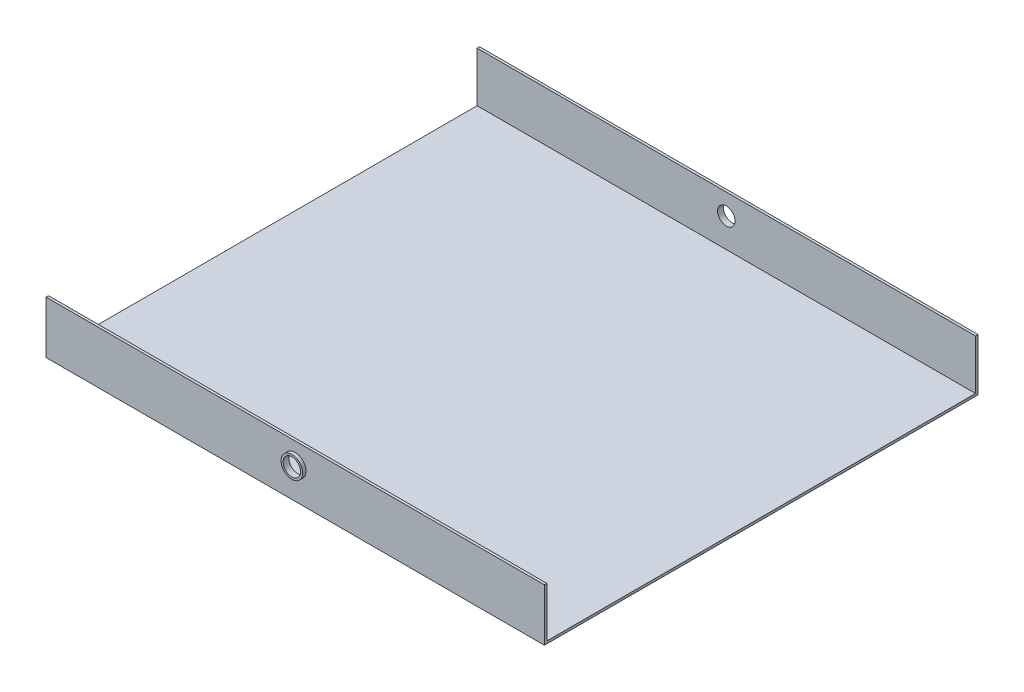
SolidWorks part; units mm, degrees
material "ABS"
ref_plane "Přední rovina" through (0, 0, 0) normal (0, 0, 1) x (1, 0, 0)
ref_plane "Horní rovina" through (0, 0, 0) normal (0, 1, 0) x (1, 0, 0)
ref_plane "Pravá rovina" through (0, 0, 0) normal (1, 0, 0) x (0, 0, -1)
sketch "Skica4" plane through (0, 0, 0) normal (1, 0, 0) x (0, 0, -1)
  line L0 (0, 0) -> (0, 71.589) construction
  line L3 (100, 28) -> (129, 28)
  line L4 (129, 28) -> (129, 58)
  line L5 (100, 28) -> (0, 28)
  dimension "D3" = 29
  dimension "D4" = 30
extrude "Vysunout tenkostěnný1" add sketch "Skica4" along normal mid plane 300 thin
mirror "Zrcadlit1" about plane through (150, 26.5, 0) normal (0, 0, 1) of "Vysunout tenkostěnný1"
sketch "Skica9" plane through (0, 0, -130.5) normal (0, 0, -1) x (-1, 0, 0)
  line L1 (-150, 26.5) -> (-150, 58) construction
  circle A0 centre (0, 45.5) radius 5.25
  dimension "D2" = 10.5
  dimension "D3" = 150
extrude "Odebrat vysunutím4" cut sketch "Skica9" against normal through all
sketch "Sketch1" plane through (0, 0, 130.5) normal (0, 0, 1) x (1, 0, 0)
  circle A0 centre (0, 45.5) radius 6.5
  circle A1 centre (0, 45.5) radius 5.25
  dimension "D1" = 13
extrude "Boss-Extrude2" add sketch "Sketch1" along normal blind 2
sketch "Sketch2" plane through (0, 0, -130.5) normal (0, 0, -1) x (-1, 0, 0)
  circle A0 centre (0, 45.5) radius 6.5
  circle A1 centre (0, 45.5) radius 5.25
  dimension "D1" = 13
extrude "Boss-Extrude3" add sketch "Sketch2" along normal blind 2
scale "Scale1" scale about centroid uniform scaling yes scale factor 8
sketch "Sketch4" plane through (0, 12.6983, 0) normal (0, 1, 0) x (1, 0, 0)
  line L0 (-573.5449, 1032) -> (-573.5449, -1032) construction
  line L1 (1200, 1032) -> (-1200, 1032) construction
  line L2 (1200, -1032) -> (-1200, -1032) construction
  line L3 (-573.5449, -1032) -> (-1200, -1032) construction
  line L4 (-1200, -1032) -> (-1200, 1032) construction
  line L5 (-1200, -1032) -> (-1200, 1032) construction
  line L6 (-1200, 1032) -> (-573.5449, 1032) construction
  line L7 (-573.5449, 1032) -> (-573.5449, -1044)
  line L8 (1200, -1044) -> (-1200, -1044) construction
  line L9 (-573.5449, -1044) -> (-1200, -1032)
  line L10 (-1200, -1032) -> (-1200, 1032)
  line L11 (-1200, 1032) -> (-573.5449, 1032)
